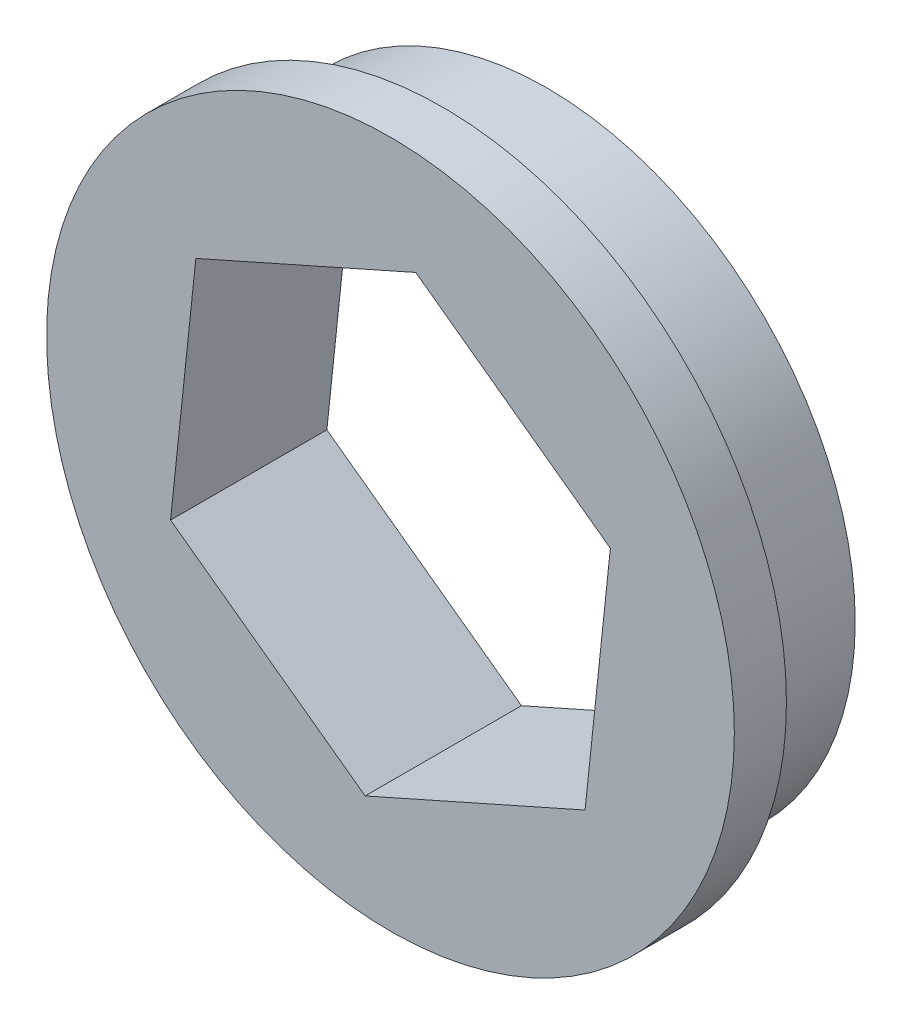
SolidWorks part; units mm, degrees
ref_plane "Front Plane" through (0, 0, 0) normal (0, 0, 1) x (1, 0, 0)
ref_plane "Top Plane" through (0, 0, 0) normal (0, 1, 0) x (1, 0, 0)
ref_plane "Right Plane" through (0, 0, 0) normal (1, 0, 0) x (0, 0, -1)
sketch "Sketch1" plane through (0, 0, 0) normal (0, 0, 1) x (1, 0, 0)
  line L1 (0.7709, 7.2917) -> (-5.9293, 4.3135)
  line L2 (-5.9293, 4.3135) -> (-6.7003, -2.9782)
  line L3 (-6.7003, -2.9782) -> (-0.7709, -7.2917)
  line L4 (-0.7709, -7.2917) -> (5.9293, -4.3135)
  line L5 (5.9293, -4.3135) -> (6.7003, 2.9782)
  line L6 (6.7003, 2.9782) -> (0.7709, 7.2917)
  circle A0 centre (0, 0) radius 6.35 construction
  circle A1 centre (0, 0) radius 9.398
  dimension "D2" = 18.796
  dimension "D1" = 12.7
extrude "Boss-Extrude1" add sketch "Sketch1" along normal blind 3.175
sketch "Sketch2" plane through (0, 0, 3.175) normal (0, 0, 1) x (1, 0, 0)
  line L1 (0.7709, 7.2917) -> (-5.9293, 4.3135)
  line L2 (-5.9293, 4.3135) -> (-6.7003, -2.9782)
  line L3 (-6.7003, -2.9782) -> (-0.7709, -7.2917)
  line L4 (-0.7709, -7.2917) -> (5.9293, -4.3135)
  line L5 (5.9293, -4.3135) -> (6.7003, 2.9782)
  line L6 (6.7003, 2.9782) -> (0.7709, 7.2917)
  circle A0 centre (0, 0) radius 6.35 construction
  circle A1 centre (0, 0) radius 10.4775
  dimension "D1" = 20.955
extrude "Boss-Extrude2" add sketch "Sketch2" along normal blind 1.5875
